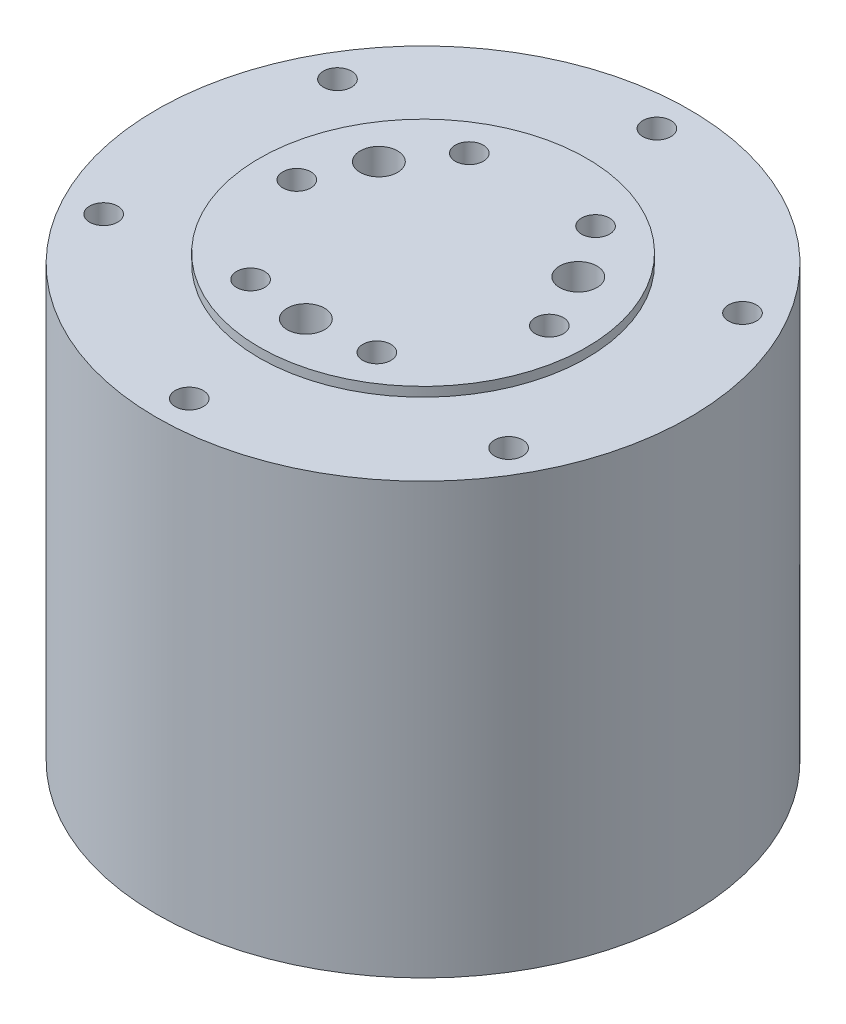
SolidWorks part; units mm, degrees
ref_plane "前视基准面" through (0, 0, 0) normal (0, 0, 1) x (1, 0, 0)
ref_plane "上视基准面" through (0, 0, 0) normal (0, 1, 0) x (1, 0, 0)
ref_plane "右视基准面" through (0, 0, 0) normal (1, 0, 0) x (0, 0, -1)
other "Configuration Table"
sketch "草图1" plane through (0, 0, 0) normal (0, 1, 0) x (1, 0, 0)
  circle A0 centre (0, 0) radius 28.5
  dimension "D1" = 57
extrude "凸台-拉伸1" add sketch "草图1" along normal blind 46
sketch "草图2" plane through (0, 46, 0) normal (0, 1, 0) x (1, 0, 0)
  circle A0 centre (0, 0) radius 17.5
  dimension "D1" = 35
extrude "凸台-拉伸2" add sketch "草图2" along normal blind 1
sketch "草图4" plane through (0, 0, 0) normal (0, -1, 0) x (1, 0, 0)
  line L0 (0, 0) -> (0, 19) construction
  line L1 (0, 0) -> (13.435, 13.435) construction
  circle A0 centre (0, 0) radius 19 construction
  circle A1 centre (13.435, 13.435) radius 1.5
  dimension "D1" = 38
  dimension "D2" = 45
  dimension "D3" = 3
extrude "切除-拉伸1" cut sketch "草图4" against normal blind 4
pattern_circular "阵列(圆周)1" count 4 over 360 about axis through (0, 0, 0) along (0, 1, 0) of "切除-拉伸1"
sketch "草图5" plane through (0, 47, 0) normal (0, 1, 0) x (1, 0, 0)
  line L0 (0, 0) -> (0, 12.15) construction
  line L1 (0, 0) -> (10.5222, 6.075) construction
  circle A0 centre (0, 0) radius 12.15 construction
  circle A1 centre (10.5222, 6.075) radius 2
  dimension "D1" = 24.3
  dimension "D3" = 4
  dimension "D2" = 60
extrude "切除-拉伸2" cut sketch "草图5" against normal blind 4
pattern_circular "阵列(圆周)2" count 3 over 360 about axis through (-0.1393, 0, 0.0804) along (0, 1, 0) of "切除-拉伸2"
sketch "草图6" plane through (0, 47, 0) normal (0, 1, 0) x (1, 0, 0)
  circle A0 centre (0, 0) radius 13.5 construction
  circle A1 centre (13.5, 0) radius 1.5
  dimension "D1" = 27
  dimension "D2" = 3
extrude "切除-拉伸3" cut sketch "草图6" against normal blind 5
pattern_circular "阵列(圆周)3" count 6 over 360 about axis through (0, 0, 0) along (0, 1, 0) of "切除-拉伸3"
sketch "草图8" plane through (0, 46, 0) normal (0, 1, 0) x (1, 0, 0)
  circle A0 centre (0, 0) radius 25 construction
  circle A1 centre (0, 25) radius 1.5
  dimension "D1" = 50
  dimension "D2" = 3
extrude "切除-拉伸4" cut sketch "草图8" against normal blind 5
pattern_circular "阵列(圆周)4" count 6 over 360 about axis through (0, 0, 0) along (0, 1, 0) of "切除-拉伸4"
